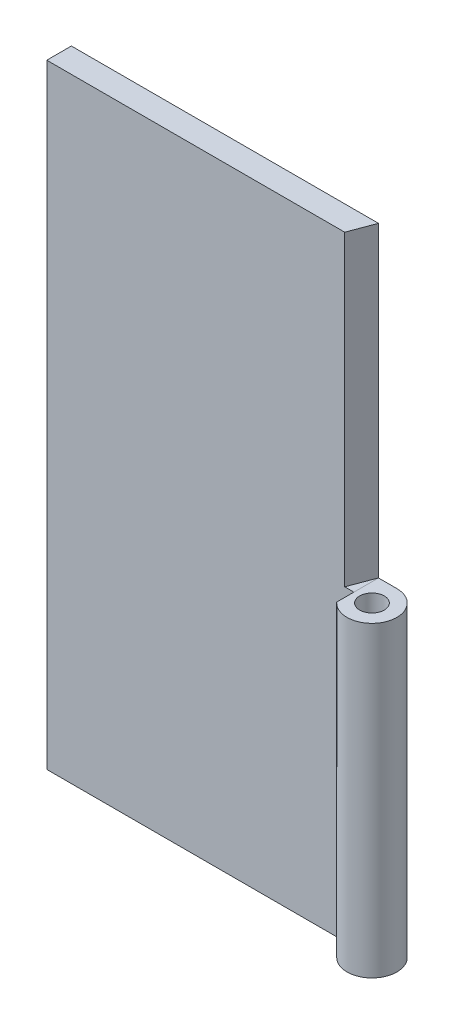
SolidWorks part; units mm, degrees
ref_plane "Front Plane" through (0, 0, 0) normal (0, 0, 1) x (1, 0, 0)
ref_plane "Top Plane" through (0, 0, 0) normal (0, 1, 0) x (1, 0, 0)
ref_plane "Right Plane" through (0, 0, 0) normal (1, 0, 0) x (0, 0, -1)
sketch "Sketch1" plane through (0, 0, 0) normal (0, 0, 1) x (1, 0, 0)
  line L1 (0, 0) -> (25, 0)
  line L2 (0, 0) -> (0, -50)
  line L3 (0, -50) -> (25, -50)
  line L4 (25, 0) -> (25, -50)
  dimension "D1" = 25
  dimension "D2" = 50
extrude "Boss-Extrude1" add sketch "Sketch1" along normal blind 2
sketch "Sketch2" plane through (0, 0, 0) normal (0, 1, 0) x (1, 0, 0)
  line L0 (25, 0) -> (26.5, 0)
  line L2 (25, 0) -> (25, -3.4)
  arc A0 (25, -3.4) -> (26.5, 0) centre (26.5, -2.0309) ccw
  dimension "D1" = 3.4
  dimension "D2" = 1.5
sketch "Sketch4" plane through (0, -50, 0) normal (0, -1, 0) x (1, 0, 0)
  line L4 (25, 0) -> (26.5, 0)
  line L5 (25, 3.4) -> (25, 0)
  line L6 (25, 0) -> (26.5, 0)
  line L7 (25, 3.4) -> (25, 0)
  arc A2 (26.5, 0) -> (25, 3.4) centre (26.5, 2.0309) ccw
  arc A3 (26.5, 0) -> (25, 3.4) centre (26.5, 2.0309) ccw
  dimension "D1" = 0
extrude "Boss-Extrude3" add sketch "Sketch4" against normal blind 25 separate body
sketch "Sketch5" plane through (0, -50, 0) normal (0, -1, 0) x (1, 0, 0)
  circle A0 centre (26.5, 2.0309) radius 1
  arc A1 (26.5, 0) -> (25, 3.4) centre (26.5, 2.0309) ccw construction
  dimension "D1" = 2
extrude "Cut-Extrude2" cut sketch "Sketch5" against normal through all
sketch "Sketch7" plane through (0, 0, 0) normal (0, 1, 0) x (1, 0, 0)
  line L1 (25, -2) -> (0, -2) construction
  line L3 (25, -2) -> (25, 0) construction
  line L4 (25, 0) -> (24.25, -2)
  line L5 (24.25, -2) -> (25, -2)
  line L6 (25, -2) -> (25, 0)
  dimension "D1" = 0.75
extrude "Cut-Extrude4" cut sketch "Sketch7" against normal up to surface (25 mm away) up to face at (26.5, -25, 1.0309)
